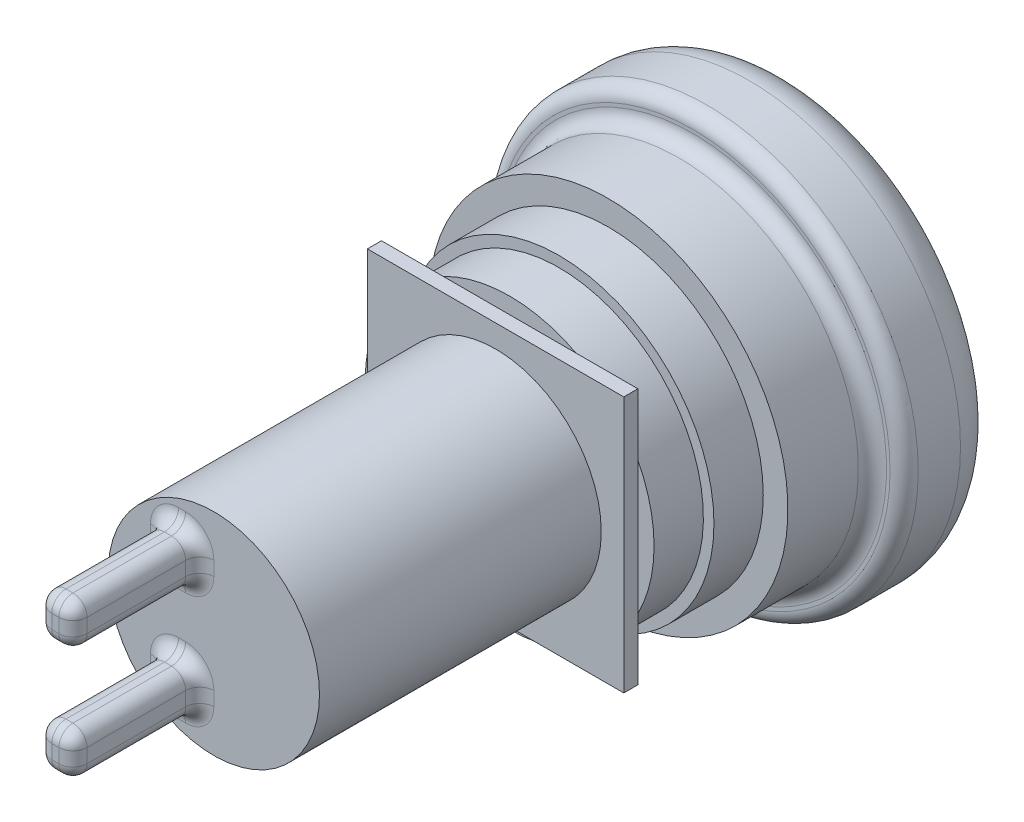
SolidWorks part; units mm, degrees
ref_plane "Front Plane" through (0, 0, 0) normal (0, 0, 1) x (1, 0, 0)
ref_plane "Top Plane" through (0, 0, 0) normal (0, 1, 0) x (1, 0, 0)
ref_plane "Right Plane" through (0, 0, 0) normal (1, 0, 0) x (0, 0, -1)
sketch "Sketch1" plane through (0, 0, 0) normal (0, 0, 1) x (1, 0, 0)
  circle A0 centre (0, 0) radius 7.5
  dimension "D1" = 15
extrude "Boss-Extrude1" add sketch "Sketch1" along normal blind 20
sketch "Sketch2" plane through (0, 0, 20) normal (0, 0, 1) x (1, 0, 0)
  line L1 (-3.5, 5.5) -> (-1, 5.5)
  line L2 (-3.5, 5.5) -> (-3.5, 2.5)
  line L3 (-3.5, 2.5) -> (-1, 2.5)
  line L4 (-1, 5.5) -> (-1, 2.5)
  line L5 (-3.5, -2.5) -> (-1, -2.5)
  line L6 (-3.5, -2.5) -> (-3.5, -5.5)
  line L7 (-3.5, -5.5) -> (-1, -5.5)
  line L8 (-1, -2.5) -> (-1, -5.5)
  circle A0 centre (0, 0) radius 7.5 construction
  dimension "D1" = 3.5
  dimension "D2" = 2.5
  dimension "D3" = 2.5
  dimension "D4" = 2.5
  dimension "D5" = 3.5
  dimension "D6" = 3
  dimension "D7" = 3
  dimension "D8" = 2.5
extrude "Boss-Extrude2" add sketch "Sketch2" along normal blind 9
sketch "Sketch3" plane through (0, 0, 0) normal (0, 0, -1) x (-1, 0, 0)
  line L1 (9.1, 9.1) -> (-9.1, 9.1)
  line L2 (9.1, 9.1) -> (9.1, -9.1)
  line L3 (9.1, -9.1) -> (-9.1, -9.1)
  line L4 (-9.1, 9.1) -> (-9.1, -9.1)
  line L5 (9.1, 9.1) -> (-9.1, -9.1) construction
  line L6 (9.1, -9.1) -> (-9.1, 9.1) construction
  point P0 (0, 0)
  dimension "D1" = 18.2
  dimension "D2" = 18.2
extrude "Boss-Extrude3" add sketch "Sketch3" along normal blind 1
sketch "Sketch4" plane through (0, 0, -1) normal (0, 0, -1) x (-1, 0, 0)
  circle A0 centre (0, 0) radius 10.25
  dimension "D1" = 20.5
extrude "Boss-Extrude4" add sketch "Sketch4" along normal blind 3.5
sketch "Sketch5" plane through (0, 0, -4.5) normal (0, 0, -1) x (-1, 0, 0)
  circle A0 centre (0, 0) radius 11
  dimension "D1" = 22
extrude "Boss-Extrude5" add sketch "Sketch5" along normal blind 3.5
sketch "Sketch6" plane through (0, 0, -8) normal (0, 0, -1) x (-1, 0, 0)
  circle A0 centre (0, 0) radius 12.75
  dimension "D1" = 25.5
extrude "Boss-Extrude6" add sketch "Sketch6" along normal blind 6
sketch "Sketch7" plane through (0, 0, -14) normal (0, 0, -1) x (-1, 0, 0)
  circle A0 centre (0, 0) radius 15
  dimension "D1" = 30
extrude "Boss-Extrude7" add sketch "Sketch7" along normal blind 7
fillet "Fillet1" radius 3 1 edges at (-15, 0, -21)
fillet "Fillet2" radius 1 2 edges at (-15, 0, -14) (-12.75, 0, -14)
fillet "Fillet3" radius 1 24 edges at (-2.25, 2.5, 20) (-2.25, 5.5, 20) (-2.25, -5.5, 20) (-2.25, -2.5, 20) (-3.5, 5.5, 24.5) (-3.5, 4, 29) (-3.5, 2.5, 24.5) (-3.5, 4, 20) (-1, 2.5, 24.5) (-1, 4, 29) (-1, 5.5, 24.5) (-1, 4, 20) (-3.5, -2.5, 24.5) (-3.5, -4, 29) (-3.5, -5.5, 24.5) (-3.5, -4, 20) (-1, -5.5, 24.5) (-1, -4, 29) (-1, -2.5, 24.5) (-1, -4, 20) (-2.25, -5.5, 29) (-2.25, -2.5, 29) (-2.25, 2.5, 29) (-2.25, 5.5, 29)
